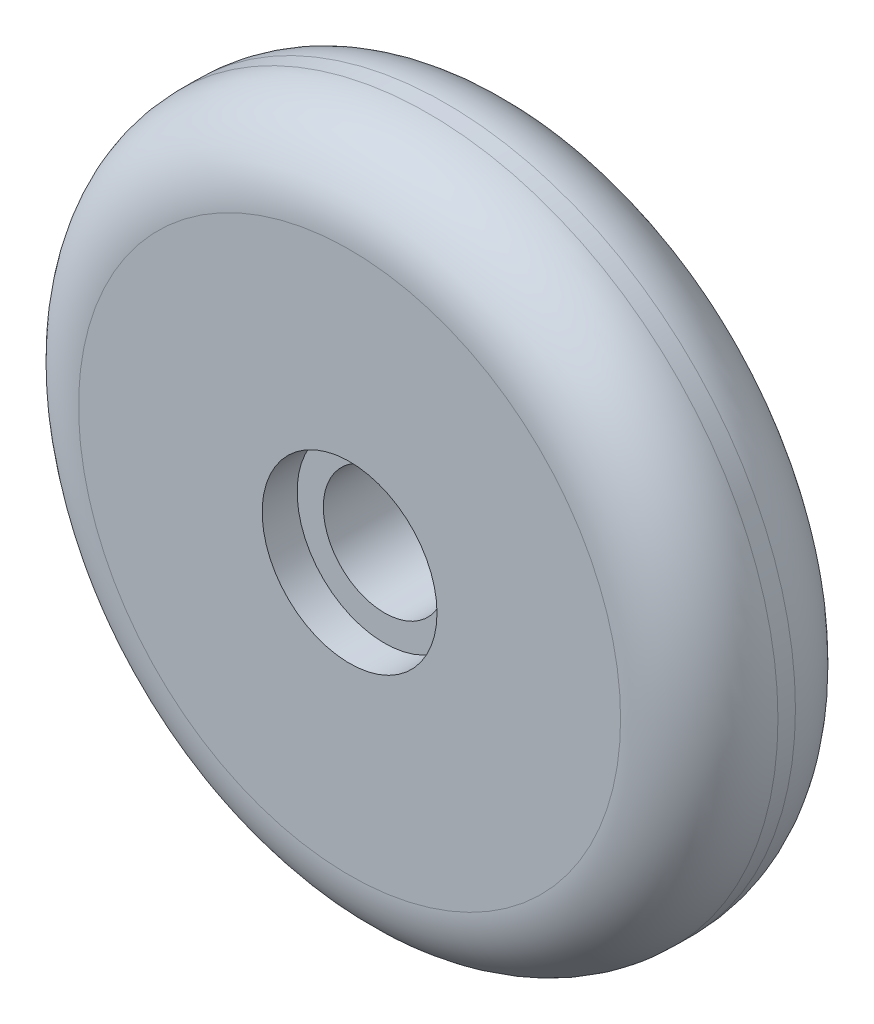
SolidWorks part; units mm, degrees
ref_plane "Front Plane" through (0, 0, 0) normal (0, 0, 1) x (1, 0, 0)
ref_plane "Top Plane" through (0, 0, 0) normal (0, 1, 0) x (1, 0, 0)
ref_plane "Right Plane" through (0, 0, 0) normal (1, 0, 0) x (0, 0, -1)
sketch "Sketch1" plane through (0, 0, 0) normal (0, 0, 1) x (1, 0, 0)
  circle A0 centre (0, 0) radius 3.5
  circle A1 centre (0, 0) radius 20
  dimension "D1" = 7
  dimension "D2" = 40
extrude "Boss-Extrude1" add sketch "Sketch1" along normal blind 10
fillet "Fillet1" radius 4.5 2 edges at (20, 0, 0) (20, 0, 10)
sketch "Sketch2" plane through (0, 0, 0) normal (0, 0, -1) x (-1, 0, 0)
  circle A0 centre (0, 0) radius 5
sketch "Sketch3" plane through (0, 0, 0) normal (0, 0, 1) x (1, 0, 0)
  circle A0 centre (0, 0) radius 5
sketch "Sketch5" plane through (0, 0, 10) normal (0, 0, 1) x (1, 0, 0)
  circle A0 centre (0, 0) radius 5
extrude "Cut-Extrude1" cut sketch "Sketch2" against normal blind 2
extrude "Cut-Extrude2" cut sketch "Sketch5" against normal blind 2
